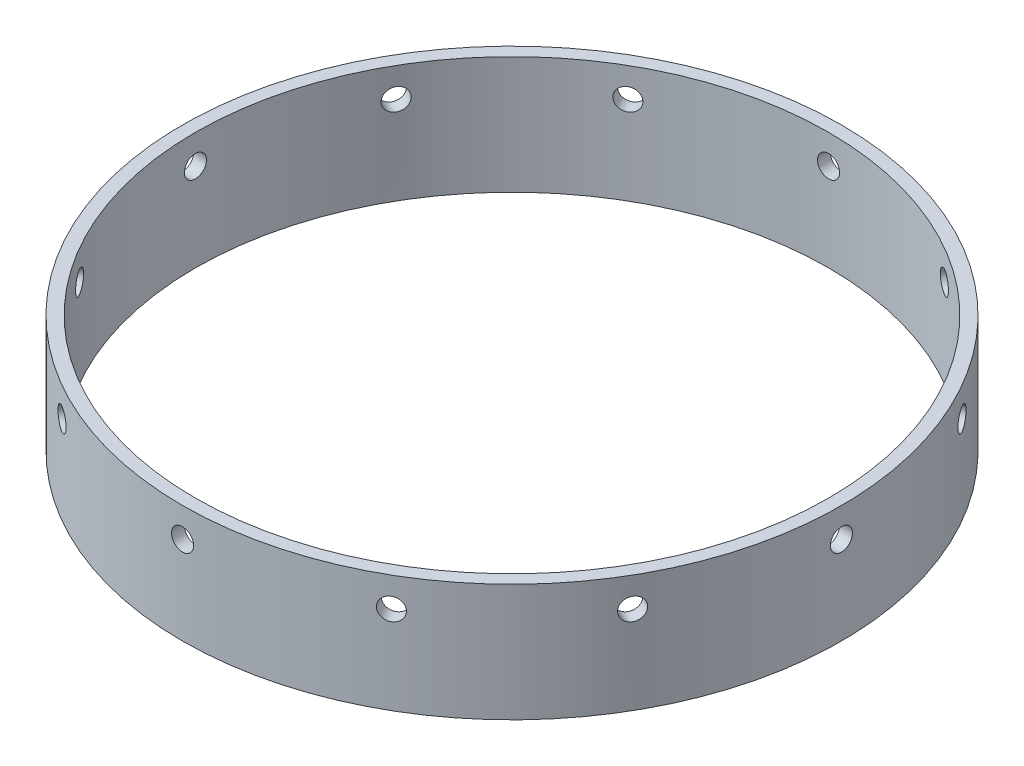
SolidWorks part; units mm, degrees
ref_plane "前视基准面" through (0, 0, 0) normal (0, 0, 1) x (1, 0, 0)
ref_plane "上视基准面" through (0, 0, 0) normal (0, 1, 0) x (1, 0, 0)
ref_plane "右视基准面" through (0, 0, 0) normal (1, 0, 0) x (0, 0, -1)
sketch "草图1" plane through (0, 0, 0) normal (0, 1, 0) x (1, 0, 0)
  circle A0 centre (0, 0) radius 44.9
  circle A1 centre (0, 0) radius 24.6 construction
  circle A2 centre (-24.6, 0) radius 2.5
  circle A3 centre (-12.3, 21.3042) radius 2.5
  circle A4 centre (12.3, 21.3042) radius 2.5
  circle A5 centre (24.6, 0) radius 2.5
  circle A6 centre (12.3, -21.3042) radius 2.5
  circle A7 centre (-12.3, -21.3042) radius 2.5
  circle A8 centre (0, 0) radius 18.4
  point P19 (0, 0)
  dimension "D1" = 6
  dimension "D2" = 89.8
extrude "凸台-拉伸1" add sketch "草图1" along normal blind 16
sketch "草图2" plane through (0, 0, 0) normal (0, -1, 0) x (1, 0, 0)
  circle A0 centre (0, 0) radius 24.6 construction
  circle A1 centre (-21.3042, -12.3) radius 4
  circle A2 centre (0, 24.6) radius 4
  circle A3 centre (21.3042, -12.3) radius 4
  point P17 (0, 0)
  dimension "D1" = 3
extrude "切除-拉伸1" cut sketch "草图2" against normal blind 3
sketch "草图4" plane through (0, 16, 0) normal (0, 1, 0) x (1, 0, 0)
  circle A0 centre (-24.6, 0) radius 4.5
  circle A1 centre (0, 0) radius 24.6 construction
  circle A2 centre (-12.3, 21.3042) radius 4.5
  circle A3 centre (12.3, 21.3042) radius 4.5
  circle A4 centre (24.6, 0) radius 4.5
  circle A5 centre (12.3, -21.3042) radius 4.5
  circle A6 centre (-12.3, -21.3042) radius 4.5
  point P16 (0, 0)
  dimension "D1" = 6
extrude "切除-拉伸2" cut sketch "草图4" against normal blind 5.1
ref_plane "基准面1" through (45, 0, 0) normal (1, 0, 0) x (0, 0, -1)
sketch "草图5" plane through (45, 0, 0) normal (1, 0, 0) x (0, 0, -1)
  circle A0 centre (0, 12) radius 1.5
extrude "切除-拉伸3" cut sketch "草图5" against normal blind 10
pattern_circular "阵列(圆周)1" count 12 every 30 about axis through (0, 0, 0) along (0, 1, 0) of "切除-拉伸3"
fillet "圆角1" radius 0.5 1 edges at (0, 16, 18.4)
sketch "Sketch1" plane through (0, 16, 0) normal (0, 1, 0) x (1, 0, 0)
  circle A0 centre (0, 0) radius 43.15
extrude "Cut-Extrude1" cut sketch "Sketch1" against normal through all
